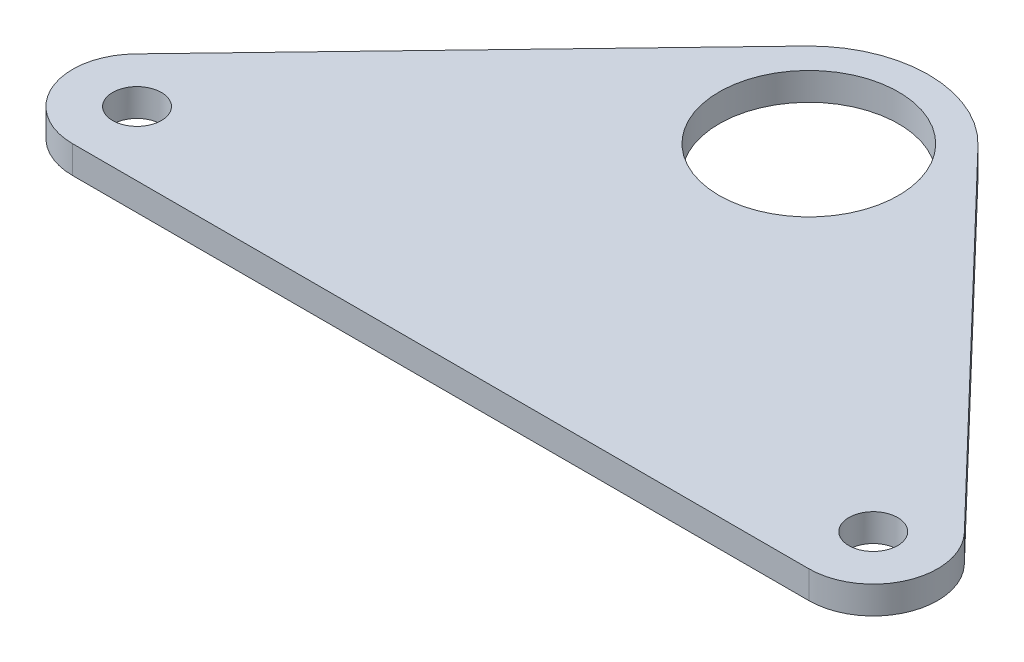
SolidWorks part; units mm, degrees
ref_plane "Front Plane" through (0, 0, 0) normal (0, 0, 1) x (1, 0, 0)
ref_plane "Top Plane" through (0, 0, 0) normal (0, 1, 0) x (1, 0, 0)
ref_plane "Right Plane" through (0, 0, 0) normal (1, 0, 0) x (0, 0, -1)
sketch "Sketch1" plane through (0, 0, 0) normal (0, 1, 0) x (1, 0, 0)
  line L0 (-40, -33) -> (40, -33) construction
  line L1 (0, -13) -> (0, -33) construction
  line L2 (-40, -33) -> (0, 0) construction
  line L3 (0, 0) -> (40, -33) construction
  line L4 (-9.3777, 9.0033) -> (-45.0495, -28.1521)
  line L5 (-40, -40) -> (40, -40)
  line L6 (45.0495, -28.1521) -> (9.3777, 9.0033)
  circle A0 centre (0, 0) radius 9.75
  circle A1 centre (0, 0) radius 13 construction
  arc A2 (-45.0495, -28.1521) -> (-40, -40) centre (-40, -33) ccw
  arc A3 (40, -40) -> (45.0495, -28.1521) centre (40, -33) ccw
  arc A4 (-9.3777, 9.0033) -> (9.3777, 9.0033) centre (0, 0) cw
  point P8 (0, -33)
  point P16 (8.2366, 10.0578)
  dimension "D1" = 19.5
  dimension "D2" = 26
  dimension "D3" = 80
  dimension "D4" = 20
  dimension "D5" = 7
extrude "Boss-Extrude1" add sketch "Sketch1" along normal blind 3
hole_wizard "M5 Clearance Hole1" positions "Sketch2" profile "Sketch3" hole size "M5" standard "ANSI Metric" end condition up to next
sketch "Sketch2" plane through (0, 3, 0) normal (0, 1, 0) x (1, 0, 0)
  point P0 (-40, -33)
  point P3 (40, -33)
sketch "Sketch3" plane through (-40, 3, 33) normal (1, 0, 0) x (0, 0, 1)
  line L0 (0, 0) -> (0, 3)
  line L1 (0, 3) -> (2.65, 3)
  line L2 (2.65, 3) -> (2.65, 0)
  line L5 (2.65, 0) -> (0, 0)
  line L11 (0, -6.35) -> (0, 107.95) construction
  dimension "Thru Hole Dia." = 5.3
  dimension "Thru Hole Depth" = 3
